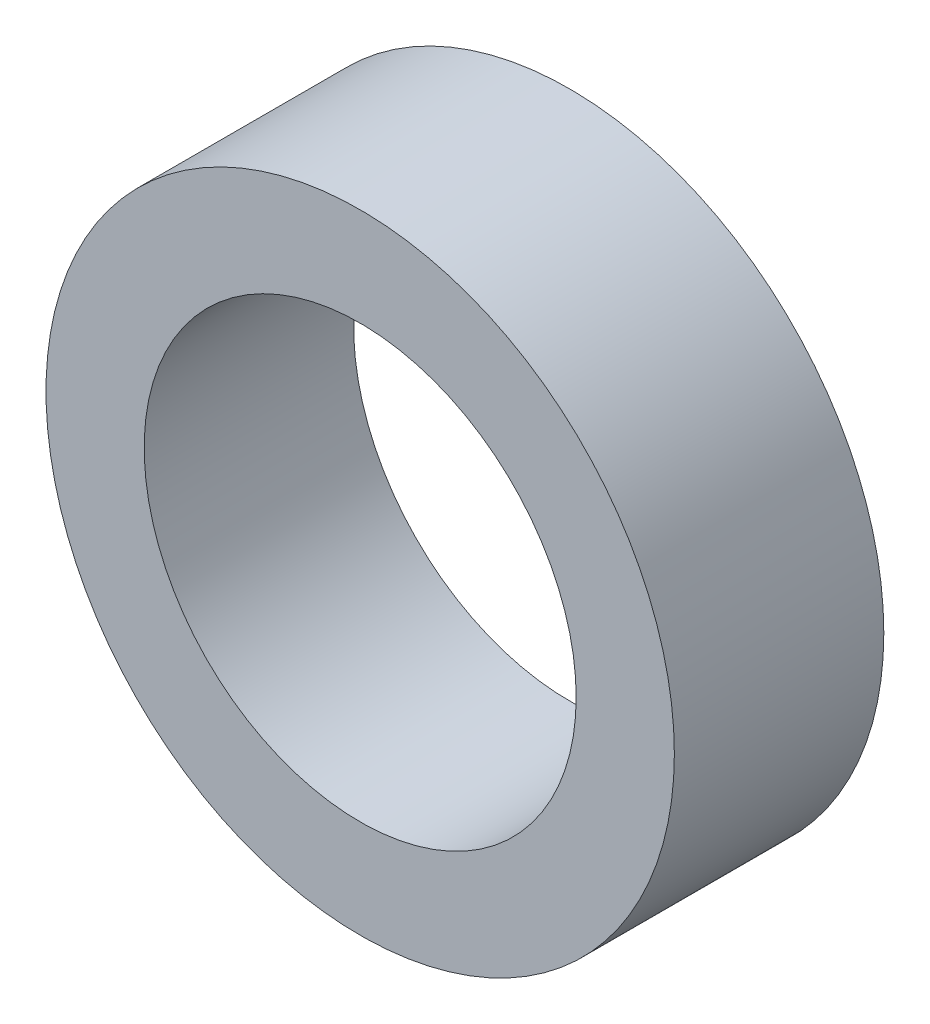
SolidWorks part; units mm, degrees
ref_plane "Front Plane" through (0, 0, 0) normal (0, 0, 1) x (1, 0, 0)
ref_plane "Top Plane" through (0, 0, 0) normal (0, 1, 0) x (1, 0, 0)
ref_plane "Right Plane" through (0, 0, 0) normal (1, 0, 0) x (0, 0, -1)
sketch "Sketch1" plane through (0, 0, 0) normal (0, 0, 1) x (1, 0, 0)
  line L0 (-28.5652, 5.9036) -> (-30.5909, 2.3102) construction
  line L1 (-30.5909, 2.3102) -> (-34.1842, 4.3359) construction
  line L2 (-28.5652, 5.9036) -> (-34.1842, 4.3359) construction
  line L3 (-30.5909, 2.3102) -> (-32.1585, 7.9293) construction
  line L4 (-35.7519, 9.955) -> (-30.1328, 11.5226) construction
  line L5 (-32.9423, 10.7388) -> (-33.267, 11.9026) construction
  circle A0 centre (-32.1585, 7.9293) radius 6
  circle A2 centre (-32.1585, 7.9293) radius 4.125
  dimension "D1" = 45
  dimension "D2" = 1.2082
extrude "Boss-Extrude1" add sketch "Sketch1" along normal blind 4
equation "\"WheelOD\"= 12"
equation "\"WheelThickness\" = 4"
equation "\"ShaftMajorDiameter\"= 8 + 0.25"
